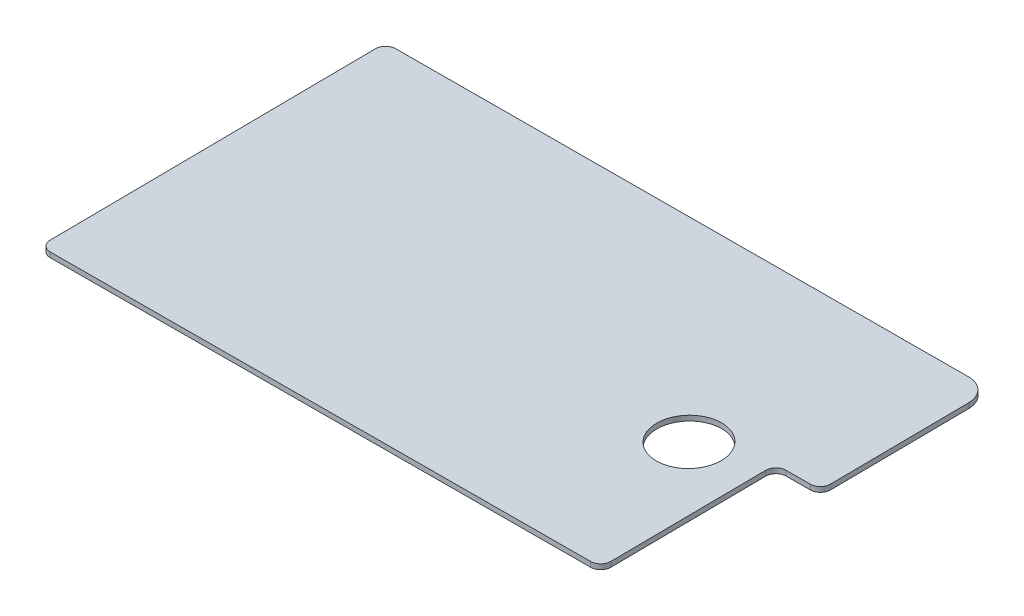
SolidWorks part; units mm, degrees
ref_plane "Front Plane" through (0, 0, 0) normal (0, 0, 1) x (1, 0, 0)
ref_plane "Top Plane" through (0, 0, 0) normal (0, 1, 0) x (1, 0, 0)
ref_plane "Right Plane" through (0, 0, 0) normal (1, 0, 0) x (0, 0, -1)
sketch "Sketch1" plane through (3.1449, -1568.3331, -7.5142) normal (-0.004, 0.9999, 0.0096) x (1, 0.004, 0)
  line L0 (3.1449, 114.3) -> (3.1449, -101.6) construction
  line L1 (253.4406, 121.8142) -> (-104.8051, 121.8142)
  line L2 (267.3049, 107.95) -> (267.3049, 21.59)
  line L3 (233.0149, -94.0858) -> (-104.8051, -94.0858)
  line L4 (-111.1551, 115.4642) -> (-111.1551, -87.7358)
  line L5 (245.7149, 15.24) -> (260.9549, 15.24)
  line L6 (254.6049, 0) -> (254.6049, 121.8142) construction
  line L7 (-111.1551, 7.5142) -> (285.75, 7.5142) construction
  line L8 (3.1449, 7.5142) -> (-111.1551, -31.8424) construction
  line L11 (239.3649, -87.7358) -> (239.3649, 8.89)
  circle A0 centre (3.1449, 7.5142) radius 84.7725
  circle A1 centre (3.1449, 7.5142) radius 95.25 construction
  circle A2 centre (5.0933, 10.8272) radius 6.35
  arc A3 (239.3649, 8.89) -> (245.7149, 15.24) centre (245.7149, 8.89) cw
  arc A4 (-104.8051, 121.8142) -> (-111.1551, 115.4642) centre (-104.8051, 115.4642) ccw
  circle A5 centre (36.7916, 87.8575) radius 6.35
  circle A6 centre (87.6527, 21.8908) radius 6.35
  arc A7 (-104.8051, -94.0858) -> (-111.1551, -87.7358) centre (-104.8051, -87.7358) cw
  arc A8 (233.0149, -94.0858) -> (239.3649, -87.7358) centre (233.0149, -87.7358) ccw
  arc A9 (260.9549, 15.24) -> (267.3049, 21.59) centre (260.9549, 21.59) ccw
  arc A10 (253.4406, 121.8142) -> (267.3049, 107.95) centre (253.4406, 107.95) cw
  circle A11 centre (254.6049, 96.4142) radius 6.35
  circle A12 centre (254.6049, 25.4) radius 6.35
  circle A13 centre (5.0933, 10.8272) radius 6.35 construction
  point P0 (3.1449, 7.5142)
  point P11 (3.1449, 7.5142)
  point P21 (235.9528, 1.1031)
  point P32 (239.3649, -94.0858)
  point P46 (43.1792, 40.1918)
  dimension "D3" = 169.545
  dimension "D5" = 190.5
  dimension "D6" = 12.7
  dimension "D7" = 114.3
  dimension "D8" = 264.16
  dimension "D11" = 6.35
  dimension "D12" = 86.36
  dimension "D14" = 12.7
  dimension "D1" = 114.3
  dimension "D2" = 101.6
  dimension "D4" = 19
  dimension "D9" = 95.25
  dimension "D10" = 27.94
  dimension "D13" = 12.7
  dimension "D15" = 25.4
  dimension "D16" = 3
extrude "Boss-Extrude1" add sketch "Sketch1" along normal up to surface (3.175 mm away) contours A7 L4 A4 L1 A10 L2 A9 L5 A3 L11 A8 L3
sketch "Sketch2" plane through (116576.9751, 1568.3331, -278544.6553) normal (-0.004, 0.9999, 0.0096) x (0.7019, -0.004, 0.7123)
  line L4 (-114.3, -107.95) -> (-114.3, 95.25)
  line L5 (257.81, -114.3) -> (-107.95, -114.3)
  line L6 (264.16, -21.59) -> (264.16, -107.95)
  line L7 (-107.95, 101.6) -> (229.87, 101.6)
  line L8 (74.93, -114.3) -> (74.93, 101.6) construction
  line L9 (-114.3, -6.35) -> (264.16, -6.35) construction
  line L11 (319.405, 146.05) -> (-169.545, 146.05)
  line L12 (319.405, 146.05) -> (319.405, -158.75)
  line L13 (319.405, -158.75) -> (-169.545, -158.75)
  line L14 (-169.545, 146.05) -> (-169.545, -158.75)
  line L15 (319.405, 146.05) -> (-169.545, -158.75) construction
  line L16 (319.405, -158.75) -> (-169.545, 146.05) construction
  point P12 (74.93, -6.35)
  dimension "D1" = 378.46
  dimension "D2" = 215.9
  dimension "D3" = 488.95
  dimension "D4" = 304.8
sketch "Sketch4" plane through (3.1576, -1568.3328, -7.5447) normal (-0.004, 0.9999, 0.0096) x (1, 0.004, 0)
  circle A2 centre (199.7476, 0.5568) radius 20.32
  dimension "D1" = 40.64
extrude "Cut-Extrude1" cut sketch "Sketch4" along normal up to surface (3.175 mm away) up to face at (134.4725, -1564.4991, -21.307)
